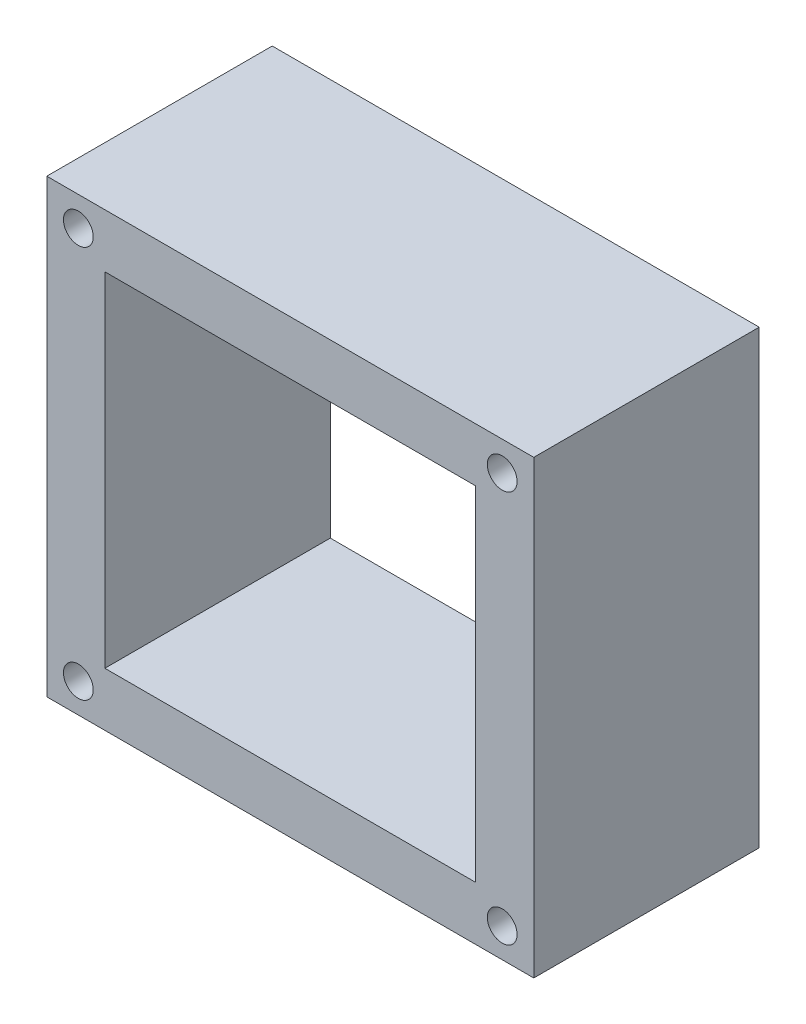
SolidWorks part; units mm, degrees
ref_plane "Front Plane" through (0, 0, 0) normal (0, 0, 1) x (1, 0, 0)
ref_plane "Top Plane" through (0, 0, 0) normal (0, 1, 0) x (1, 0, 0)
ref_plane "Right Plane" through (0, 0, 0) normal (1, 0, 0) x (0, 0, -1)
sketch "Sketch1" plane through (0, 0, 0) normal (0, 0, 1) x (1, 0, 0)
  line L0 (105, -50) -> (-67, -50) construction
  line L1 (54, 50) -> (-54, 50)
  line L2 (54, 50) -> (54, -50)
  line L3 (54, -50) -> (-54, -50)
  line L4 (-54, 50) -> (-54, -50)
  line L5 (54, 50) -> (-54, -50) construction
  line L6 (54, -50) -> (-54, 50) construction
  line L7 (54, 27) -> (54, 47) construction
  line L9 (-41.1207, -38.0747) -> (41.1207, -38.0747)
  line L10 (-41.1207, -38.0747) -> (-41.1207, 38.0747)
  line L11 (-41.1207, 38.0747) -> (41.1207, 38.0747)
  line L12 (41.1207, -38.0747) -> (41.1207, 38.0747)
  line L13 (-41.1207, -38.0747) -> (41.1207, 38.0747) construction
  line L14 (-41.1207, 38.0747) -> (41.1207, -38.0747) construction
  circle A0 centre (47, 43.5) radius 3.3 construction
  circle A1 centre (47, -43.5) radius 3.3 construction
  circle A2 centre (-47, -43.5) radius 3.3 construction
  circle A3 centre (-47, 43.5) radius 3.3 construction
  circle A4 centre (47, 43.5) radius 3.3
  circle A5 centre (47, -43.5) radius 3.3
  circle A6 centre (-47, -43.5) radius 3.3
  circle A7 centre (-47, 43.5) radius 3.3
  circle A8 centre (47, -43.5) radius 5.5 construction
  point P0 (0, 0)
  point P22 (0, 0)
  dimension "D1" = 8
extrude "Boss-Extrude1" add sketch "Sketch1" along normal blind 50
